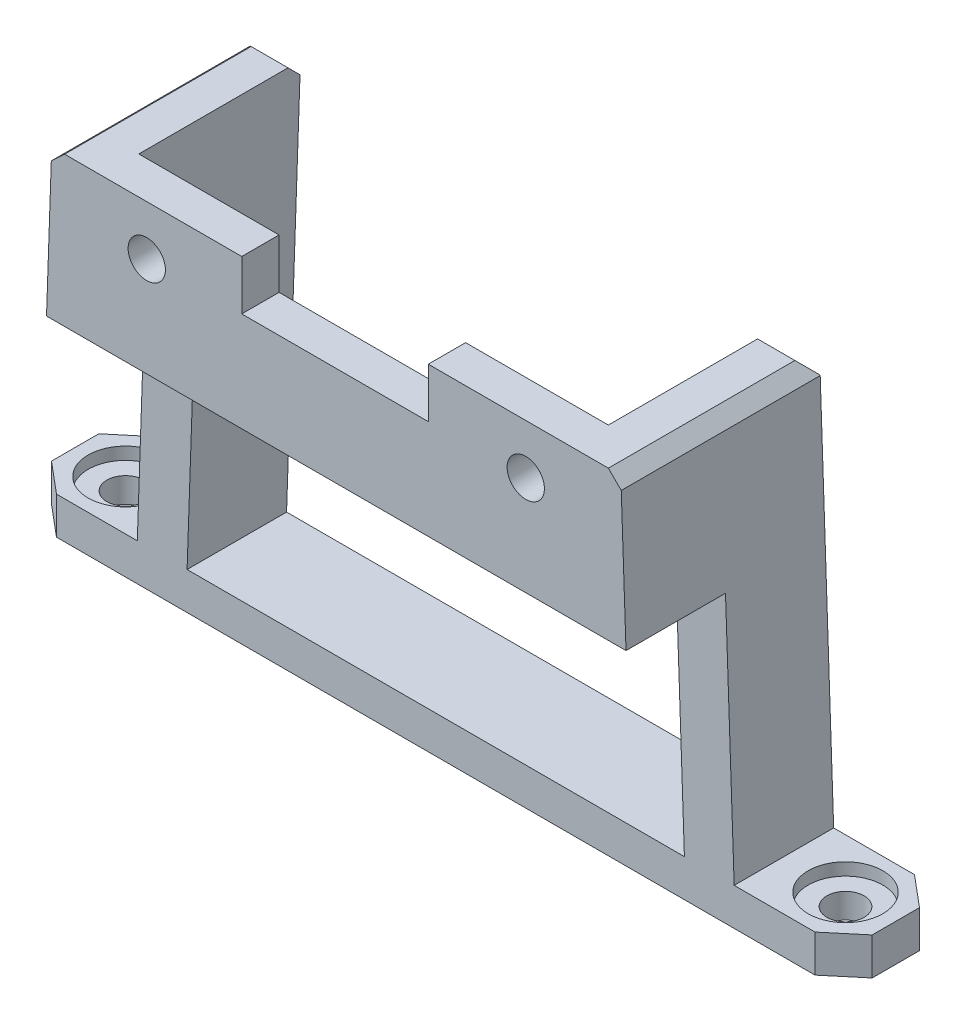
SolidWorks part; units mm, degrees
ref_plane "Front Plane" through (0, 0, 0) normal (0, 0, 1) x (1, 0, 0)
ref_plane "Top Plane" through (0, 0, 0) normal (0, 1, 0) x (1, 0, 0)
ref_plane "Right Plane" through (0, 0, 0) normal (1, 0, 0) x (0, 0, -1)
sketch "Sketch1" plane through (0, 0, 0) normal (0, 1, 0) x (1, 0, 0)
  line L0 (-28.953, 0) -> (28.953, 0) construction
  line L1 (-33, -4) -> (33, -4)
  line L2 (-33, -4) -> (-33, 4)
  line L3 (-33, 4) -> (33, 4)
  line L4 (33, -4) -> (33, 4)
  line L5 (-33, -4) -> (33, 4) construction
  line L6 (-33, 4) -> (33, -4) construction
  circle A0 centre (-28.953, 0) radius 1.5
  circle A1 centre (28.953, 0) radius 1.5
  point P0 (0, 0)
  point P10 (0, 0)
  dimension "D4" = 3
  dimension "D1" = 66
  dimension "D2" = 8
  dimension "D3" = 57.906
  dimension "D5" = 4
extrude "Boss-Extrude1" add sketch "Sketch1" along normal blind 3
sketch "Sketch4" plane through (0, 0, 4) normal (0, 0, 1) x (1, 0, 0)
  line L1 (-33, 3) -> (-33, 0) construction
  line L13 (-24, 3) -> (-22.8825, 35)
  line L14 (-33, 3) -> (33, 3) construction
  line L15 (-22.8825, 35) -> (-18.8801, 35)
  line L16 (-18.8801, 35) -> (-19.9976, 3)
  line L17 (-19.9976, 3) -> (-24, 3)
  dimension "D1" = 32
  dimension "D2" = 9
  dimension "D3" = 4
  dimension "D4" = 92
extrude "Boss-Extrude4" add sketch "Sketch4" against normal up to surface (8 mm away) up to face at (0, 1.5, -4)
mirror "Mirror1" about plane through (0, 0, 0) normal (1, 0, 0) of "Boss-Extrude4"
sketch "Sketch6" plane through (0, 0, 4) normal (0, 0, 1) x (1, 0, 0)
  line L0 (-22.8825, 35) -> (22.8825, 35)
  line L1 (22.8825, 35) -> (23.3016, 23)
  line L2 (22.8825, 35) -> (24, 3) construction
  line L3 (23.3016, 23) -> (-23.3016, 23)
  line L4 (-22.8825, 35) -> (-24, 3) construction
  line L5 (-23.3016, 23) -> (-22.8825, 35)
  dimension "D1" = 12
extrude "Boss-Extrude6" add sketch "Sketch6" along normal blind 8
sketch "Sketch7" plane through (0, 3, 0) normal (0, 1, 0) x (1, 0, 0)
  circle A0 centre (-28.953, 0) radius 3
  circle A1 centre (28.953, 0) radius 3
  dimension "D1" = 6
extrude "Cut-Extrude1" cut sketch "Sketch7" against normal blind 1
sketch "Sketch8" plane through (0, 0, 12) normal (0, 0, 1) x (1, 0, 0)
  line L0 (-7.6, 35) -> (-7.6, 31)
  line L1 (22.8825, 35) -> (-22.8825, 35) construction
  line L2 (-7.6, 31) -> (7.4, 31)
  line L3 (7.4, 31) -> (7.4, 35)
  line L4 (7.4, 35) -> (-7.6, 35)
  dimension "D1" = 15
  dimension "D2" = 7.6
  dimension "D3" = 4
extrude "Cut-Extrude2" cut sketch "Sketch8" against normal up to surface (8 mm away) up to face at (0, 29, 4)
sketch "Sketch9" plane through (0, 0, 4) normal (0, 0, -1) x (-1, 0, 0)
  line L0 (-19.2991, 23) -> (19.2991, 23)
  line L1 (19.2991, 23) -> (18.8801, 35)
  line L2 (18.8801, 35) -> (-18.8801, 35)
  line L3 (-18.8801, 35) -> (-19.2991, 23)
extrude "Cut-Extrude3" cut sketch "Sketch9" against normal blind 5
chamfer "Chamfer2" distance 1 angle 45 4 edges at (-22.8825, 35, 4) (-20.8813, 35, -4) (22.8825, 35, 4) (20.8813, 35, -4)
sketch "Sketch10" plane through (0, 0, 9) normal (0, 0, -1) x (-1, 0, 0)
  line L0 (-15.24, 31) -> (15.24, 31) construction
  line L1 (-7.4, 35) -> (-18.8801, 35) construction
  circle A0 centre (-15.24, 31) radius 1.5
  circle A1 centre (15.24, 31) radius 1.5
  point P4 (0, 31)
  dimension "D1" = 3
  dimension "D2" = 4
  dimension "D3" = 30.48
extrude "Cut-Extrude4" cut sketch "Sketch10" against normal up to surface (3 mm away) up to face at (-0.0362, 31.5964, 12)
sketch "Sketch13" plane through (0, 3, 0) normal (0, 1, 0) x (1, 0, 0)
  line L0 (-30.5, 4) -> (-33, 1.9023)
  line L1 (-24, 4) -> (-33, 4) construction
  line L2 (-33, 4) -> (-33, -4) construction
  line L3 (-33, 1.9023) -> (-33, 4)
  line L4 (-33, 4) -> (-30.5, 4)
  line L5 (-30.5, -4) -> (-33, -1.9023)
  line L6 (-33, -4) -> (-24, -4) construction
  line L7 (-33, -1.9023) -> (-33, -4)
  line L8 (-33, -4) -> (-30.5, -4)
  line L9 (30.5, -4) -> (33, -1.9023)
  line L10 (24, -4) -> (33, -4) construction
  line L11 (33, -4) -> (33, 4) construction
  line L12 (33, -1.9023) -> (33, -4)
  line L13 (33, -4) -> (30.5, -4)
  line L14 (30.5, 4) -> (33, 1.9023)
  line L15 (33, 4) -> (24, 4) construction
  line L16 (33, 1.9023) -> (33, 4)
  line L17 (33, 4) -> (30.5, 4)
  dimension "D1" = 50
  dimension "D2" = 50
  dimension "D3" = 50
  dimension "D4" = 50
  dimension "D5" = 2.5
extrude "Cut-Extrude5" cut sketch "Sketch13" against normal up to surface (3 mm away) up to face at (-28.953, 0, 1.5)
